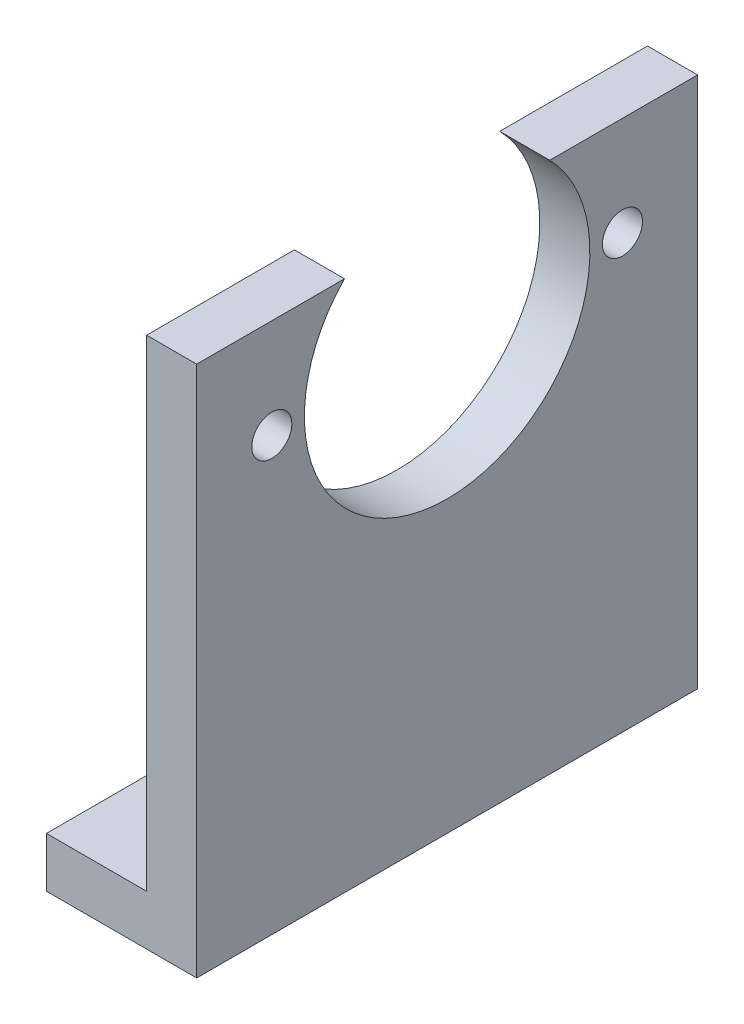
SolidWorks part; units mm, degrees
ref_plane "前视基准面" through (0, 0, 0) normal (0, 0, 1) x (1, 0, 0)
ref_plane "上视基准面" through (0, 0, 0) normal (0, 1, 0) x (1, 0, 0)
ref_plane "右视基准面" through (0, 0, 0) normal (1, 0, 0) x (0, 0, -1)
sketch "草图2" plane through (0, 0, 0) normal (1, 0, 0) x (0, 0, -1)
  line L0 (-17.5, 0) -> (17.5, 0) construction
  line L1 (0, 0) -> (0, -50000) construction
  line L2 (-25, 9.9031) -> (-10.2465, 9.9031)
  line L3 (25, 9.9031) -> (25, -43.1669)
  line L4 (-25, 9.9031) -> (-25, -43.1669)
  line L5 (-25, -43.1669) -> (25, -43.1669)
  line L6 (10.2465, 9.9031) -> (25, 9.9031)
  circle A0 centre (17.5, 0) radius 2
  circle A1 centre (-17.5, 0) radius 2
  arc A2 (-10.2465, 9.9031) -> (10.2465, 9.9031) centre (0, 0) ccw
  point P4 (0, 0)
  point P11 (0, 9.9031)
  dimension "D2" = 4
  dimension "D3" = 4
  dimension "D6" = 28.5
  dimension "D1" = 35
  dimension "D4" = 50
  dimension "D5" = 53.07
extrude "凸台-拉伸2" add sketch "草图2" along normal blind 5
sketch "草图4" plane through (0, 0, 0) normal (-1, 0, 0) x (0, 0, 1)
  line L0 (25, 9.9031) -> (25, -43.1669) construction
  line L1 (-25, -43.1669) -> (25, -43.1669)
  line L2 (-25, -43.1669) -> (-25, -38.1669)
  line L3 (-25, -38.1669) -> (25, -38.1669)
  line L4 (25, -43.1669) -> (25, -38.1669)
  dimension "D1" = 5
extrude "凸台-拉伸3" add sketch "草图4" along normal blind 10
